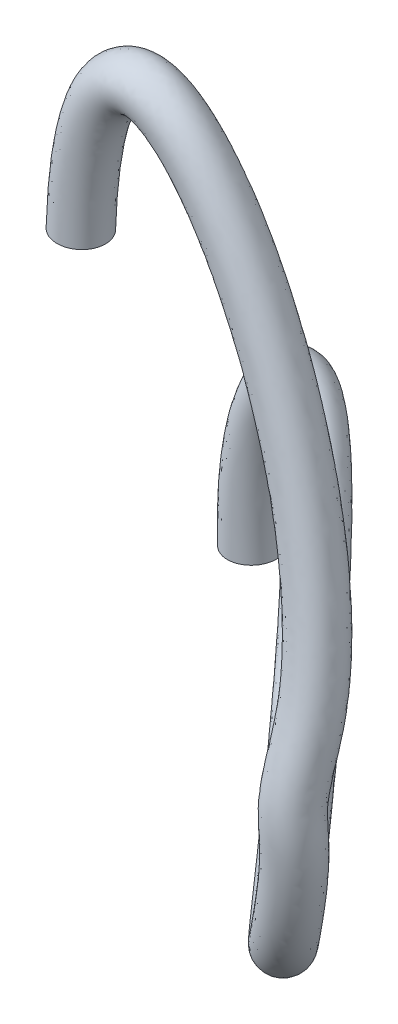
SolidWorks part; units mm, degrees
ref_plane "Front Plane" through (0, 0, 0) normal (0, 0, 1) x (1, 0, 0)
ref_plane "Top Plane" through (0, 0, 0) normal (0, 1, 0) x (1, 0, 0)
ref_plane "Right Plane" through (0, 0, 0) normal (1, 0, 0) x (0, 0, -1)
sketch3d "3DSketch1"
  line L0 (-13.0348, -226.5128, 50.1244) -> (-13.0348, -231.5128, 50.1244) construction
  line L1 (8.1713, -217.5128, 69.6412) -> (8.1713, -215.0128, 69.6412) construction
  line L2 (-2.4638, -201.3193, 67.6695) -> (-2.4638, -216.3193, 67.6695) construction
  line L3 (-13.0348, -238.3321, 50.1244) -> (-13.0348, -226.5128, 50.1244) construction
  spline S0 degree 3 poles (-13.0348, -226.5128, 50.1244) (-13.1083, -221.5978, 50.2087) (-8.4577, -213.6463, 49.4147) (5.6227, -228.4728, 68.7189) (8.3807, -216.9916, 69.6916) (8.088, -215.0267, 69.8036) (8.8133, -205.8038, 66.3209) (-1.9752, -185.8375, 67.635) (-2.4638, -201.3193, 67.6695) knots 0 0 0 0 0.110506 0.429031 0.469068 0.506234 0.559792 1 1 1 1
  point P0 (-13.0348, -226.5128, 50.1244)
  point P1 (-13.0348, -226.5128, 50.1244)
  point P4 (8.1713, -215.0128, 69.6412)
  point P5 (8.1713, -217.5128, 69.6412)
  point P8 (-2.4638, -201.3193, 67.6695)
  point P13 (0, 0, 0)
  point P15 (-10.1667, -218.9288, 51.0238)
sweep "Sweep1" add path "3DSketch1" circular profile diameter 2 parameters "D3"=2
